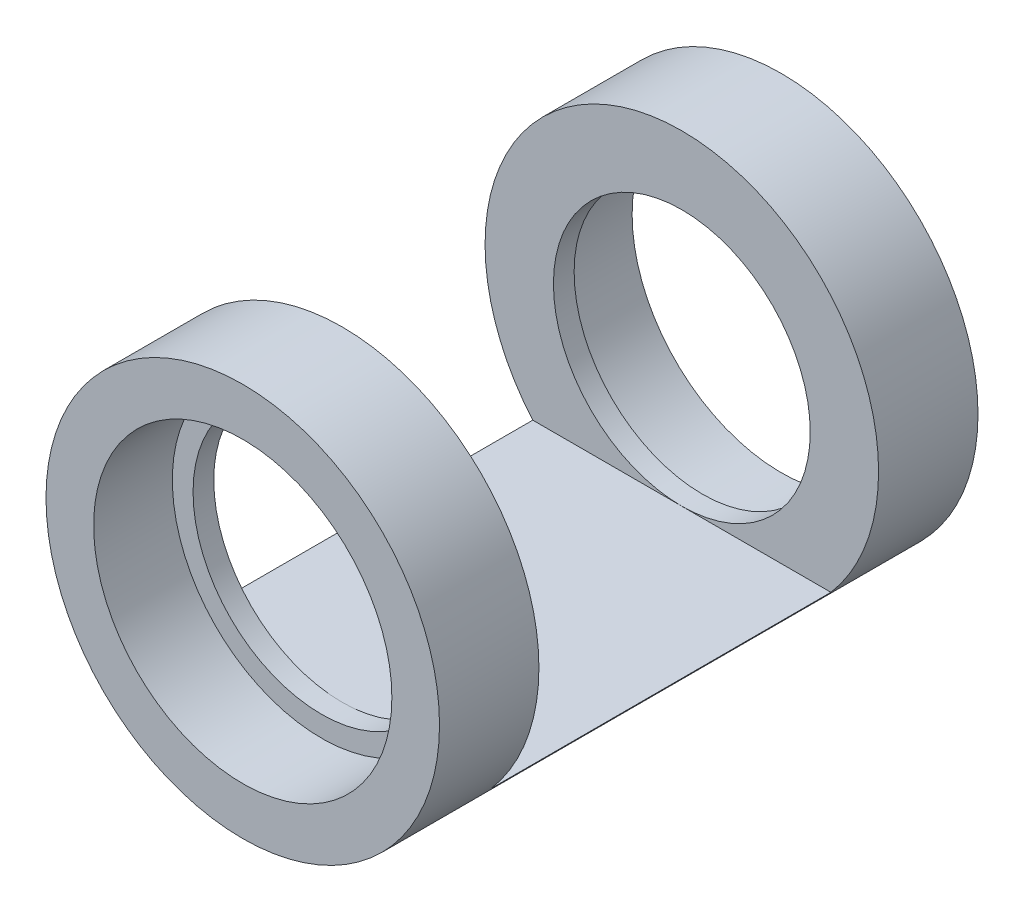
SolidWorks part; units mm, degrees
ref_plane "前视基准面" through (0, 0, 0) normal (0, 0, 1) x (1, 0, 0)
ref_plane "上视基准面" through (0, 0, 0) normal (0, 1, 0) x (1, 0, 0)
ref_plane "右视基准面" through (0, 0, 0) normal (1, 0, 0) x (0, 0, -1)
other "Configuration Table"
sketch "草图1" plane through (0, 0, 0) normal (0, 0, 1) x (1, 0, 0)
  circle A0 centre (0, 0) radius 47.5
  dimension "D1" = 95
extrude "凸台-拉伸1" add sketch "草图1" along normal mid plane 130
sketch "草图2" plane through (0, 0, 0) normal (0, 0, 1) x (1, 0, 0)
  line L0 (-35.9896, -31) -> (35.9896, -31)
  circle A0 centre (0, 0) radius 47.5 construction
  circle A2 centre (0, 0) radius 47.5
  arc A3 (35.9896, -31) -> (-35.9896, -31) centre (0, 0) ccw
  dimension "D1" = 31
  dimension "D2" = 0
extrude "切除-拉伸1" cut sketch "草图2" against normal mid plane 82
sketch "草图3" plane through (0, 0, -65) normal (0, 0, -1) x (-1, 0, 0)
  circle A0 centre (0, 0) radius 36
  dimension "D1" = 72
extrude "切除-拉伸2" cut sketch "草图3" against normal blind 19
sketch "草图4" plane through (0, 0, -46) normal (0, 0, -1) x (-1, 0, 0)
  circle A0 centre (0, 0) radius 31
  dimension "D1" = 62
extrude "切除-拉伸3" cut sketch "草图4" against normal through all
sketch "草图5" plane through (0, 0, 65) normal (0, 0, 1) x (1, 0, 0)
  circle A0 centre (0, 0) radius 36
  dimension "D1" = 72
extrude "切除-拉伸4" cut sketch "草图5" against normal blind 19
